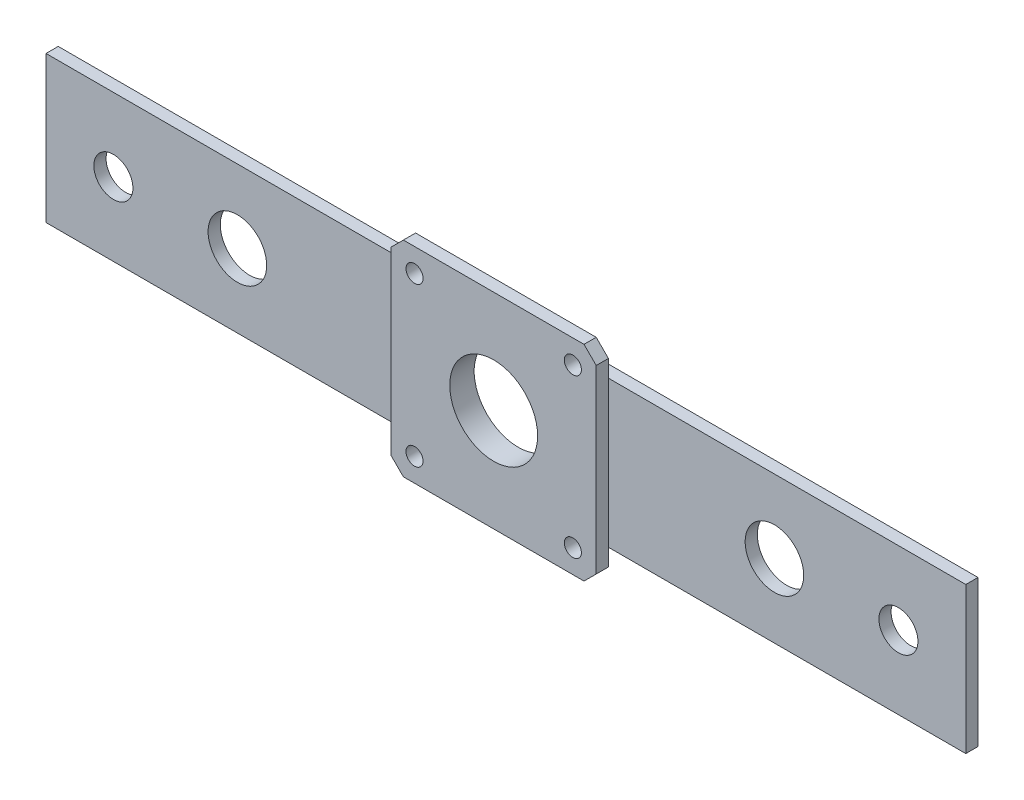
SolidWorks part; units mm, degrees
ref_plane "Front Plane" through (0, 0, 0) normal (0, 0, 1) x (1, 0, 0)
ref_plane "Top Plane" through (0, 0, 0) normal (0, 1, 0) x (1, 0, 0)
ref_plane "Right Plane" through (0, 0, 0) normal (1, 0, 0) x (0, 0, -1)
sketch "Sketch1" plane through (0, 0, 0) normal (0, 0, 1) x (1, 0, 0)
  line L1 (-94.2, 15) -> (94.2, 15)
  line L2 (-94.2, 15) -> (-94.2, -15)
  line L3 (-94.2, -15) -> (94.2, -15)
  line L4 (94.2, 15) -> (94.2, -15)
  line L5 (-94.2, 15) -> (94.2, -15) construction
  line L6 (-94.2, -15) -> (94.2, 15) construction
  point P0 (0, 0)
  dimension "D1" = 188.4
  dimension "D2" = 30
extrude "Boss-Extrude1" add sketch "Sketch1" along normal blind 2.5
sketch "Sketch2" plane through (0, 0, 2.5) normal (0, 0, 1) x (1, 0, 0)
  line L0 (0, 0) -> (0, 57.1618) construction
  line L1 (94.2, 15) -> (-94.2, 15) construction
  line L2 (-94.2, -15) -> (94.2, -15) construction
  line L4 (-94.2, 15) -> (-94.2, -15) construction
  circle A0 centre (-55, 0) radius 6
  circle A1 centre (55, 0) radius 6
  circle A2 centre (0, 0) radius 6
  circle A3 centre (-80.4, 0) radius 4
  circle A4 centre (80.4, 0) radius 4
  dimension "D1" = 12
  dimension "D3" = 12
  dimension "D5" = 8
  dimension "D4" = 13.8
  dimension "D2" = 110
  dimension "D6" = 15
  dimension "D7" = 15
  dimension "D8" = 94.2
  dimension "D9" = 15
  dimension "D10" = 39.2
extrude "Cut-Extrude2" cut sketch "Sketch2" against normal through all
sketch "Sketch3" plane through (0, 0, 2.5) normal (0, 0, 1) x (1, 0, 0)
  line L0 (-21, 18.5) -> (-18.5, 21)
  line L1 (-18.5, 21) -> (18.5, 21)
  line L2 (-21, 18.5) -> (-21, -18.5)
  line L3 (-18.5, -21) -> (18.5, -21)
  line L4 (21, 18.5) -> (21, -18.5)
  line L5 (-21, 21) -> (21, -21) construction
  line L6 (-21, -21) -> (21, 21) construction
  line L7 (18.5, 21) -> (21, 18.5)
  line L8 (18.5, -21) -> (21, -18.5)
  line L9 (-21, -18.5) -> (-18.5, -21)
  circle A0 centre (16.2145, 16.2145) radius 1.75
  circle A1 centre (-16.2145, -16.2145) radius 1.75
  circle A2 centre (16.2145, -16.2145) radius 1.75
  circle A3 centre (-16.2145, 16.2145) radius 1.75
  point P0 (0, 0)
  dimension "D3" = 3.5
  dimension "D5" = 0
  dimension "D6" = 3.5
  dimension "D1" = 42
  dimension "D2" = 42
  dimension "D4" = 5
  dimension "D7" = 5
extrude "Boss-Extrude4" add sketch "Sketch3" along normal blind 2.5
sketch "Sketch5" plane through (0, 0, 2.5) normal (0, 0, -1) x (-1, 0, 0)
  circle A0 centre (0, 0) radius 9
  dimension "D1" = 18
extrude "Cut-Extrude5" cut sketch "Sketch5" against normal blind 14.5 and the other way blind 14.5
